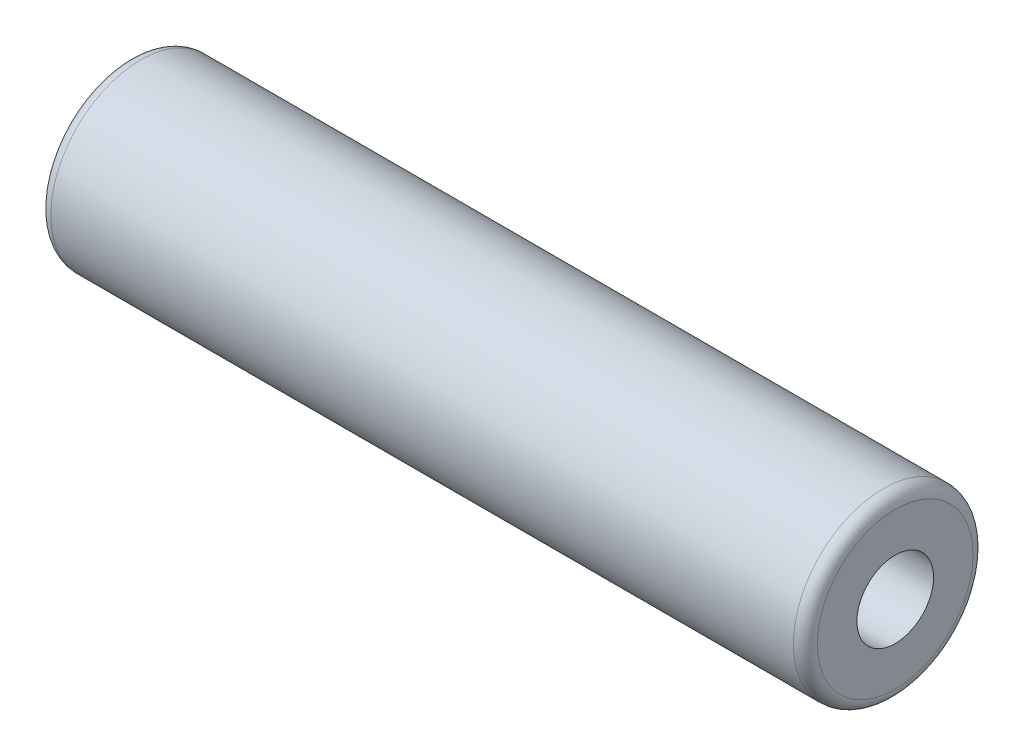
SolidWorks part; units mm, degrees
ref_plane "Front Plane" through (0, 0, 0) normal (0, 0, 1) x (1, 0, 0)
ref_plane "Top Plane" through (0, 0, 0) normal (0, 1, 0) x (1, 0, 0)
ref_plane "Right Plane" through (0, 0, 0) normal (1, 0, 0) x (0, 0, -1)
sketch "Sketch1" plane through (0, 0, 0) normal (1, 0, 0) x (0, 0, -1)
  circle A0 centre (0, 0) radius 4.7625
  dimension "D1" = 9.525
extrude "Boss-Extrude1" add sketch "Sketch1" along normal mid plane 40.64
sketch "Sketch3" plane through (20.32, 0, 0) normal (1, 0, 0) x (0, 0, -1)
  circle A0 centre (0, 0) radius 2.032
  dimension "D1" = 4.064
extrude "Cut-Extrude1" cut sketch "Sketch3" against normal through all
fillet "Fillet1" radius 0.635 2 edges at (-20.32, 0, -4.7625) (20.32, 0, -4.7625)
